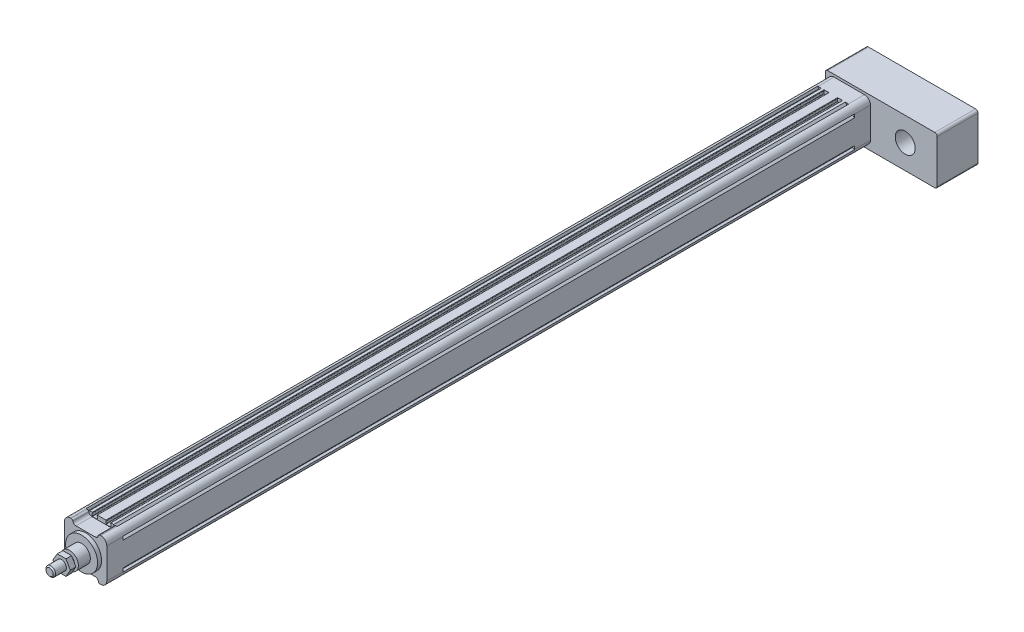
SolidWorks part; units mm, degrees
ref_plane "Front" through (0, 0, 0) normal (0, 0, 1) x (1, 0, 0)
ref_plane "Top" through (0, 0, 0) normal (0, 1, 0) x (1, 0, 0)
ref_plane "Right" through (0, 0, 0) normal (1, 0, 0) x (0, 0, -1)
sketch "草图1" plane through (0, 0, 0) normal (0, 0, 1) x (1, 0, 0)
  line L0 (19.7737, 3) -> (23.3, 3)
  line L1 (23.3, 3) -> (23.3, -3)
  line L2 (23.3, -3) -> (19.7737, -3)
  line L3 (-19.7737, -3) -> (-23.3, -3)
  line L4 (-23.3, -3) -> (-23.3, 3)
  line L5 (-23.3, 3) -> (-19.7737, 3)
  line L6 (-18.2, 24) -> (-19.4434, 26.4869)
  line L7 (-26.4869, 19.4434) -> (-24, 18.2)
  line L8 (-24, 18.2) -> (-24, 17.1)
  line L9 (-24, 17.1) -> (-26.5, 15)
  line L10 (-26.5, 15) -> (-26.5, -15)
  line L11 (-26.5, -15) -> (-24, -17.1)
  line L12 (-24, -17.1) -> (-24, -18.2)
  line L13 (-24, -18.2) -> (-26.4869, -19.4434)
  line L14 (-19.4434, -26.4869) -> (-18.2, -24)
  line L15 (-18.2, -24) -> (-17.1, -24)
  line L16 (-17.1, -24) -> (-15, -26.5)
  line L17 (-15, -26.5) -> (-11.65, -26.5)
  line L18 (-11.25, -26.1) -> (-11.25, -25.6)
  line L19 (-11.65, -25.2) -> (-11.75, -25.2)
  line L20 (-11.75, -25.2) -> (-11.75, -22.4)
  line L21 (-11.35, -22) -> (-5.65, -22)
  line L22 (-5.25, -22.4) -> (-5.25, -25.2)
  line L23 (-5.25, -25.2) -> (-5.35, -25.2)
  line L24 (-5.75, -25.6) -> (-5.75, -26.1)
  line L25 (-5.35, -26.5) -> (5.35, -26.5)
  line L26 (5.75, -26.1) -> (5.75, -25.6)
  line L27 (5.35, -25.2) -> (5.25, -25.2)
  line L28 (5.25, -25.2) -> (5.25, -22.4)
  line L29 (5.65, -22) -> (11.35, -22)
  line L30 (11.75, -22.4) -> (11.75, -25.2)
  line L31 (11.75, -25.2) -> (11.65, -25.2)
  line L32 (11.25, -25.6) -> (11.25, -26.1)
  line L33 (11.65, -26.5) -> (15, -26.5)
  line L34 (15, -26.5) -> (17.1, -24)
  line L35 (17.1, -24) -> (18.2, -24)
  line L36 (18.2, -24) -> (19.4434, -26.4869)
  line L37 (26.4869, -19.4434) -> (24, -18.2)
  line L38 (24, -18.2) -> (24, -17.1)
  line L39 (24, -17.1) -> (26.5, -15)
  line L40 (26.5, -15) -> (26.5, 15)
  line L41 (26.5, 15) -> (24, 17.1)
  line L42 (24, 17.1) -> (24, 18.2)
  line L43 (24, 18.2) -> (26.4869, 19.4434)
  line L44 (19.4434, 26.4869) -> (18.2, 24)
  line L45 (18.2, 24) -> (17.1, 24)
  line L46 (17.1, 24) -> (15, 26.5)
  line L47 (15, 26.5) -> (11.65, 26.5)
  line L48 (11.25, 26.1) -> (11.25, 25.6)
  line L49 (11.65, 25.2) -> (11.75, 25.2)
  line L50 (11.75, 25.2) -> (11.75, 22.4)
  line L51 (11.35, 22) -> (5.65, 22)
  line L52 (5.25, 22.4) -> (5.25, 25.2)
  line L53 (5.25, 25.2) -> (5.35, 25.2)
  line L54 (5.75, 25.6) -> (5.75, 26.1)
  line L55 (5.35, 26.5) -> (-5.35, 26.5)
  line L56 (-5.75, 26.1) -> (-5.75, 25.6)
  line L57 (-5.35, 25.2) -> (-5.25, 25.2)
  line L58 (-5.25, 25.2) -> (-5.25, 22.4)
  line L59 (-5.65, 22) -> (-11.35, 22)
  line L60 (-11.75, 22.4) -> (-11.75, 25.2)
  line L61 (-11.75, 25.2) -> (-11.65, 25.2)
  line L62 (-11.25, 25.6) -> (-11.25, 26.1)
  line L63 (-11.65, 26.5) -> (-15, 26.5)
  line L64 (-15, 26.5) -> (-17.1, 24)
  line L65 (-17.1, 24) -> (-18.2, 24)
  arc A0 (19.7737, 3) -> (-19.7737, 3) centre (0, 0) ccw
  arc A1 (-19.7737, -3) -> (19.7737, -3) centre (0, 0) ccw
  circle A2 centre (19, 19) radius 2.1
  circle A3 centre (19, -19) radius 2.1
  circle A4 centre (-19, -19) radius 2.1
  circle A5 centre (-19, 19) radius 2.1
  arc A6 (-19.4434, 26.4869) -> (-26.4869, 19.4434) centre (-19, 19) ccw
  arc A7 (-26.4869, -19.4434) -> (-19.4434, -26.4869) centre (-19, -19) ccw
  arc A8 (-11.65, -26.5) -> (-11.25, -26.1) centre (-11.65, -26.1) ccw
  arc A9 (-11.25, -25.6) -> (-11.65, -25.2) centre (-11.65, -25.6) ccw
  arc A10 (-11.35, -22) -> (-11.75, -22.4) centre (-11.35, -22.4) ccw
  arc A11 (-5.25, -22.4) -> (-5.65, -22) centre (-5.65, -22.4) ccw
  arc A12 (-5.35, -25.2) -> (-5.75, -25.6) centre (-5.35, -25.6) ccw
  arc A13 (-5.75, -26.1) -> (-5.35, -26.5) centre (-5.35, -26.1) ccw
  arc A14 (5.35, -26.5) -> (5.75, -26.1) centre (5.35, -26.1) ccw
  arc A15 (5.75, -25.6) -> (5.35, -25.2) centre (5.35, -25.6) ccw
  arc A16 (5.65, -22) -> (5.25, -22.4) centre (5.65, -22.4) ccw
  arc A17 (11.75, -22.4) -> (11.35, -22) centre (11.35, -22.4) ccw
  arc A18 (11.65, -25.2) -> (11.25, -25.6) centre (11.65, -25.6) ccw
  arc A19 (11.25, -26.1) -> (11.65, -26.5) centre (11.65, -26.1) ccw
  arc A20 (19.4434, -26.4869) -> (26.4869, -19.4434) centre (19, -19) ccw
  arc A21 (26.4869, 19.4434) -> (19.4434, 26.4869) centre (19, 19) ccw
  arc A22 (11.65, 26.5) -> (11.25, 26.1) centre (11.65, 26.1) ccw
  arc A23 (11.25, 25.6) -> (11.65, 25.2) centre (11.65, 25.6) ccw
  arc A24 (11.35, 22) -> (11.75, 22.4) centre (11.35, 22.4) ccw
  arc A25 (5.25, 22.4) -> (5.65, 22) centre (5.65, 22.4) ccw
  arc A26 (5.35, 25.2) -> (5.75, 25.6) centre (5.35, 25.6) ccw
  arc A27 (5.75, 26.1) -> (5.35, 26.5) centre (5.35, 26.1) ccw
  arc A28 (-5.35, 26.5) -> (-5.75, 26.1) centre (-5.35, 26.1) ccw
  arc A29 (-5.75, 25.6) -> (-5.35, 25.2) centre (-5.35, 25.6) ccw
  arc A30 (-5.65, 22) -> (-5.25, 22.4) centre (-5.65, 22.4) ccw
  arc A31 (-11.75, 22.4) -> (-11.35, 22) centre (-11.35, 22.4) ccw
  arc A32 (-11.65, 25.2) -> (-11.25, 25.6) centre (-11.65, 25.6) ccw
  arc A33 (-11.25, 26.1) -> (-11.65, 26.5) centre (-11.65, 26.1) ccw
extrude "凸台-拉伸1" add sketch "草图1" along normal blind 915
sketch "草图6" plane through (0, 0, 915) normal (0, 0, 1) x (1, 0, 0)
  line L0 (0, 0) -> (19, 0) construction
  line L2 (-26.5, -19) -> (-26.5, 19)
  line L3 (-19, 26.5) -> (-17.9161, 26.5)
  line L4 (26.5, -19) -> (26.5, 19)
  line L5 (-26.5, -26.5) -> (26.5, 26.5) construction
  line L6 (-26.5, 26.5) -> (26.5, -26.5) construction
  line L7 (-12, 21.5) -> (12, 21.5)
  line L9 (19, 26.5) -> (17.9161, 26.5)
  line L10 (19, -26.5) -> (17.9161, -26.5)
  line L11 (-12, -21.5) -> (12, -21.5)
  line L12 (-19, -26.5) -> (-17.9161, -26.5)
  arc A0 (12, 21.5) -> (15.9441, 24.8333) centre (12, 25.5) ccw
  arc A1 (-15.9441, 24.8333) -> (-12, 21.5) centre (-12, 25.5) ccw
  arc A2 (-15.9441, 24.8333) -> (-17.9161, 26.5) centre (-17.9161, 24.5) ccw
  arc A3 (15.9441, 24.8333) -> (17.9161, 26.5) centre (17.9161, 24.5) cw
  arc A4 (-26.5, -19) -> (-19, -26.5) centre (-19, -19) ccw
  arc A5 (19, -26.5) -> (26.5, -19) centre (19, -19) ccw
  arc A6 (26.5, 19) -> (19, 26.5) centre (19, 19) ccw
  arc A7 (-26.5, 19) -> (-19, 26.5) centre (-19, 19) cw
  arc A8 (15.9441, -24.8333) -> (17.9161, -26.5) centre (17.9161, -24.5) ccw
  arc A9 (12, -21.5) -> (15.9441, -24.8333) centre (12, -25.5) cw
  arc A10 (-15.9441, -24.8333) -> (-12, -21.5) centre (-12, -25.5) cw
  arc A11 (-15.9441, -24.8333) -> (-17.9161, -26.5) centre (-17.9161, -24.5) cw
  point P0 (0, 0)
  point P9 (0, 21.5)
  point P13 (20, 20.8461)
  point P16 (-12, 20.8461)
  dimension "D5" = 4
  dimension "D6" = 2
  dimension "D7" = 2
  dimension "D9" = 7.5
  dimension "D1" = 53
  dimension "D2" = 53
  dimension "D3" = 26.5
  dimension "D4" = 24
  dimension "D8" = 5
extrude "凸台-拉伸2" add sketch "草图6" along normal blind 20
sketch "草图7" plane through (0, 0, 935) normal (0, 0, 1) x (1, 0, 0)
  circle A0 centre (0, 0) radius 20
  dimension "D1" = 40
extrude "凸台-拉伸3" add sketch "草图7" along normal blind 5
sketch "草图9" plane through (0, 0, 940) normal (0, 0, 1) x (1, 0, 0)
  circle A0 centre (0, 0) radius 11
  dimension "D1" = 22
extrude "凸台-拉伸4" add sketch "草图9" along normal blind 15
sketch "草图10" plane through (0, 0, 955) normal (0, 0, 1) x (1, 0, 0)
  circle A0 centre (0, 0) radius 6
  dimension "D1" = 12
extrude "凸台-拉伸5" add sketch "草图10" along normal blind 25
sketch "草图11" plane through (0, 0, 0) normal (0, 0, -1) x (-1, 0, 0)
  line L1 (-19, -26.5) -> (19, -26.5)
  line L2 (-26.5, -19) -> (-26.5, 19)
  line L3 (-19, 26.5) -> (19, 26.5)
  line L4 (26.5, -19) -> (26.5, 19)
  line L5 (-26.5, -26.5) -> (26.5, 26.5) construction
  line L6 (-26.5, 26.5) -> (26.5, -26.5) construction
  arc A0 (-26.5, -19) -> (-19, -26.5) centre (-19, -19) ccw
  arc A1 (19, -26.5) -> (26.5, -19) centre (19, -19) ccw
  arc A2 (26.5, 19) -> (19, 26.5) centre (19, 19) ccw
  arc A3 (-26.5, 19) -> (-19, 26.5) centre (-19, 19) cw
  point P0 (0, 0)
  dimension "D3" = 7.5
  dimension "D1" = 53
  dimension "D2" = 53
extrude "凸台-拉伸6" add sketch "草图11" along normal blind 20
sketch "草图12" plane through (0, 0, -20) normal (0, 0, -1) x (-1, 0, 0)
  line L1 (-107, -30.4042) -> (27, -30.4042)
  line L2 (-110, -27.4042) -> (-110, 26.5958)
  line L3 (-107, 29.5958) -> (27, 29.5958)
  line L4 (30, -27.4042) -> (30, 26.5958)
  line L5 (-110, -30.4042) -> (30, 29.5958) construction
  line L6 (-110, 29.5958) -> (30, -30.4042) construction
  arc A0 (27, 29.5958) -> (30, 26.5958) centre (27, 26.5958) cw
  arc A1 (30, -27.4042) -> (27, -30.4042) centre (27, -27.4042) cw
  arc A2 (-110, -27.4042) -> (-107, -30.4042) centre (-107, -27.4042) ccw
  arc A3 (-110, 26.5958) -> (-107, 29.5958) centre (-107, 26.5958) cw
  point P0 (-40, -0.4042)
  dimension "D4" = 3
  dimension "D1" = 60
  dimension "D2" = 140
  dimension "D3" = 30
extrude "凸台-拉伸7" add sketch "草图12" along normal blind 51
sketch "草图13" plane through (0, 0, -20) normal (0, 0, 1) x (1, 0, 0)
  circle A0 centre (70, 0) radius 12.5
  dimension "D2" = 25
  dimension "D1" = 70
extrude "切除-拉伸2" cut sketch "草图13" against normal blind 30
hole_wizard "M6 螺纹孔1" positions "草图14" profile "草图15" tap size "M6" standard "GB"
sketch "草图14" plane through (0, 0, -71) normal (0, 0, -1) x (-1, 0, 0)
  line L0 (30, -27.4042) -> (30, 26.5958) construction
  point P0 (19, -19)
  dimension "D1" = 11
  dimension "D2" = 19
sketch "草图15" plane through (-19, -19, -71) normal (1, 0, 0) x (0, 1, 0)
  line L0 (0, 0) -> (0, 16.5022)
  line L1 (0, 16.5022) -> (2.5, 15)
  line L2 (2.5, 15) -> (2.5, 0)
  line L5 (2.5, 0) -> (0, 0)
  line L10 (0, 16.5022) -> (-2.5, 15) construction
  line L11 (0, -6.35) -> (0, 107.95) construction
  dimension "螺纹孔钻头直径" = 5
  dimension "螺纹孔钻头深度" = 15
  dimension "导头角度" = 118
cosmetic thread "孔螺蚊线4" parameters "D1"=12, "D2"=6
pattern_linear "阵列(线性)1" count 2 spacing 38 along (0, 1, 0) count 2 spacing 38 along (1, 0, 0) of "M6 螺纹孔1"
hole_wizard "M6 螺纹孔2" positions "草图16" profile "草图17" tap size "M6" standard "GB"
sketch "草图16" plane through (0, 0, -71) normal (0, 0, -1) x (-1, 0, 0)
  circle A1 centre (-19, 19) radius 2.5 construction
  circle A2 centre (-19, -19) radius 2.5 construction
  point P0 (-84, -19)
  point P2 (-84, 19)
  dimension "D3" = 65
  dimension "D1" = 19
  dimension "D2" = 19
  dimension "D4" = 65
sketch "草图17" plane through (84, -19, -71) normal (1, 0, 0) x (0, 1, 0)
  line L0 (0, 0) -> (0, 16.5022)
  line L1 (0, 16.5022) -> (2.5, 15)
  line L2 (2.5, 15) -> (2.5, 0)
  line L5 (2.5, 0) -> (0, 0)
  line L10 (0, 16.5022) -> (-2.5, 15) construction
  line L11 (0, -6.35) -> (0, 107.95) construction
  dimension "螺纹孔钻头直径" = 5
  dimension "螺纹孔钻头深度" = 15
  dimension "导头角度" = 118
cosmetic thread "孔螺蚊线5" parameters "D1"=12, "D2"=6
cosmetic thread "孔螺蚊线6" parameters "D1"=12, "D2"=6
hole_wizard "M6 螺纹孔3" positions "草图19" profile "草图20" tap size "M6" standard "GB"
sketch "草图19" plane through (-26.5, 0, 0) normal (-1, 0, 0) x (0, 0, 1)
  line L0 (935, 19) -> (935, -19) construction
  point P0 (925, 11)
  point P2 (925, -11)
  dimension "D1" = 10
  dimension "D2" = 10
  dimension "D3" = 22
  dimension "D4" = 11
sketch "草图20" plane through (-26.5, 11, 925) normal (0, 1, 0) x (0, 0, 1)
  line L0 (0, 0) -> (0, 16.5022)
  line L1 (0, 16.5022) -> (2.5, 15)
  line L2 (2.5, 15) -> (2.5, 0)
  line L5 (2.5, 0) -> (0, 0)
  line L10 (0, 16.5022) -> (-2.5, 15) construction
  line L11 (0, -6.35) -> (0, 107.95) construction
  dimension "螺纹孔钻头直径" = 5
  dimension "螺纹孔钻头深度" = 15
  dimension "导头角度" = 118
cosmetic thread "孔螺蚊线7" parameters "D1"=12, "D2"=6
cosmetic thread "孔螺蚊线8" parameters "D1"=12, "D2"=6
hole_wizard "M6 螺纹孔4" positions "草图21" profile "草图22" tap size "M6" standard "GB"
sketch "草图21" plane through (-26.5, 0, 0) normal (-1, 0, 0) x (0, 0, 1)
  line L0 (-20, -27.4042) -> (-20, 26.5958) construction
  line L1 (-20, -19) -> (-20, 19) construction
  point P0 (-10, 11)
  point P2 (-10, -11)
  dimension "D1" = 10
  dimension "D2" = 10
  dimension "D3" = 11
  dimension "D4" = 11
sketch "草图22" plane through (-26.5, 11, -10) normal (0, 1, 0) x (0, 0, 1)
  line L0 (0, 0) -> (0, 16.5022)
  line L1 (0, 16.5022) -> (2.5, 15)
  line L2 (2.5, 15) -> (2.5, 0)
  line L5 (2.5, 0) -> (0, 0)
  line L10 (0, 16.5022) -> (-2.5, 15) construction
  line L11 (0, -6.35) -> (0, 107.95) construction
  dimension "螺纹孔钻头直径" = 5
  dimension "螺纹孔钻头深度" = 15
  dimension "导头角度" = 118
cosmetic thread "孔螺蚊线9" parameters "D1"=12, "D2"=6
cosmetic thread "孔螺蚊线10" parameters "D1"=12, "D2"=6
chamfer "倒角1" distance 1.5 angle 45 1 edges at (6, 0, 980)
sketch "草图23" plane through (0, 0, 955) normal (0, 0, 1) x (1, 0, 0)
  line L1 (10.9697, 0) -> (5.4848, 9.5)
  line L2 (5.4848, 9.5) -> (-5.4848, 9.5)
  line L3 (-5.4848, 9.5) -> (-10.9697, 0)
  line L4 (-10.9697, 0) -> (-5.4848, -9.5)
  line L5 (-5.4848, -9.5) -> (5.4848, -9.5)
  line L6 (5.4848, -9.5) -> (10.9697, 0)
  circle A0 centre (0, 0) radius 9.5 construction
  dimension "D1" = 19
extrude "凸台-拉伸8" add sketch "草图23" along normal blind 7 from offset 3
